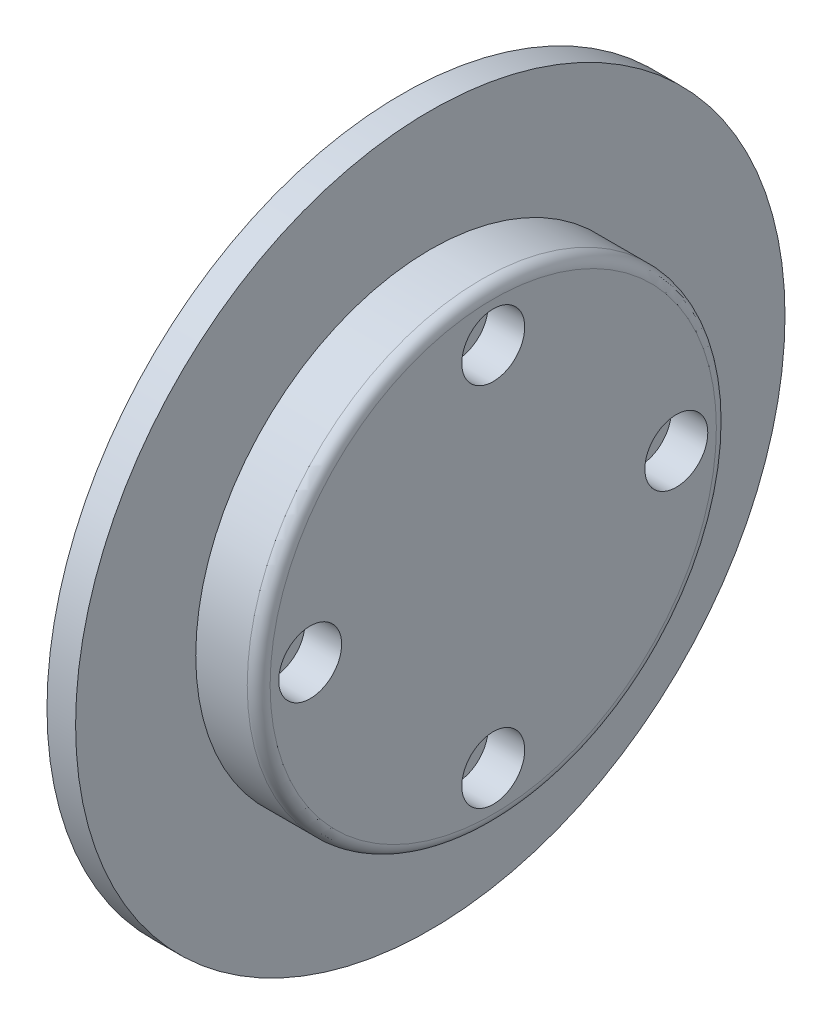
SolidWorks part; units mm, degrees
ref_plane "Front Plane" through (0, 0, 0) normal (0, 0, 1) x (1, 0, 0)
ref_plane "Top Plane" through (0, 0, 0) normal (0, 1, 0) x (1, 0, 0)
ref_plane "Right Plane" through (0, 0, 0) normal (1, 0, 0) x (0, 0, -1)
sketch "Sketch1" plane through (0, 0, 0) normal (0, 0, 1) x (1, 0, 0)
  line L0 (0, 0) -> (0, 62)
  line L1 (0, 62) -> (5, 62)
  line L2 (5, 62) -> (5, 41)
  line L3 (5, 41) -> (16, 41)
  line L4 (16, 41) -> (16, 0)
  line L5 (16, 0) -> (0, 0) construction
  line L6 (0, 0) -> (16, 0)
  dimension "D1" = 16
  dimension "D2" = 5
  dimension "D3" = 124
  dimension "D4" = 82
revolve "Revolve1" add sketch "Sketch1" angle 360 about L5
sketch "Sketch3" plane through (0, 0, 0) normal (-1, 0, 0) x (0, 0, 1)
  circle A0 centre (0, 0) radius 21
  dimension "D1" = 42
extrude "Cut-Extrude1" cut sketch "Sketch3" against normal blind 12
fillet "Fillet1" radius 1 1 edges at (12, 0, 21)
fillet "Fillet2" radius 2 1 edges at (16, 0, -41)
hole_wizard "CBORE for M6 Hex Socket Head Cap Screw1" positions "Sketch6" profile "Sketch7" counterbore size "M6" standard "DIN" end condition through all
sketch "Sketch6" plane through (16, 0, 0) normal (1, 0, 0) x (0, 0, -1)
  circle A0 centre (0, 0) radius 32 construction
  point P0 (0, -32)
  point P2 (32, 0)
  point P4 (0, 32)
  point P6 (-32, 0)
  dimension "D1" = 64
sketch "Sketch7" plane through (16, -32, 0) normal (0, 1, 0) x (0, 0, -1)
  line L0 (0, 0) -> (0, 16)
  line L1 (0, 16) -> (3.3, 16)
  line L3 (3.3, 16) -> (3.3, 6.4)
  line L4 (3.3, 6.4) -> (5.5, 6.4)
  line L5 (5.5, 6.4) -> (5.5, 0)
  line L7 (5.5, 0) -> (0, 0)
  line L11 (0, -6.35) -> (0, 107.95) construction
  dimension "Thru Hole Dia." = 6.6
  dimension "Thru Hole Depth" = 16
  dimension "C'Bore Dia." = 11
  dimension "C'Bore Depth" = 6.4
